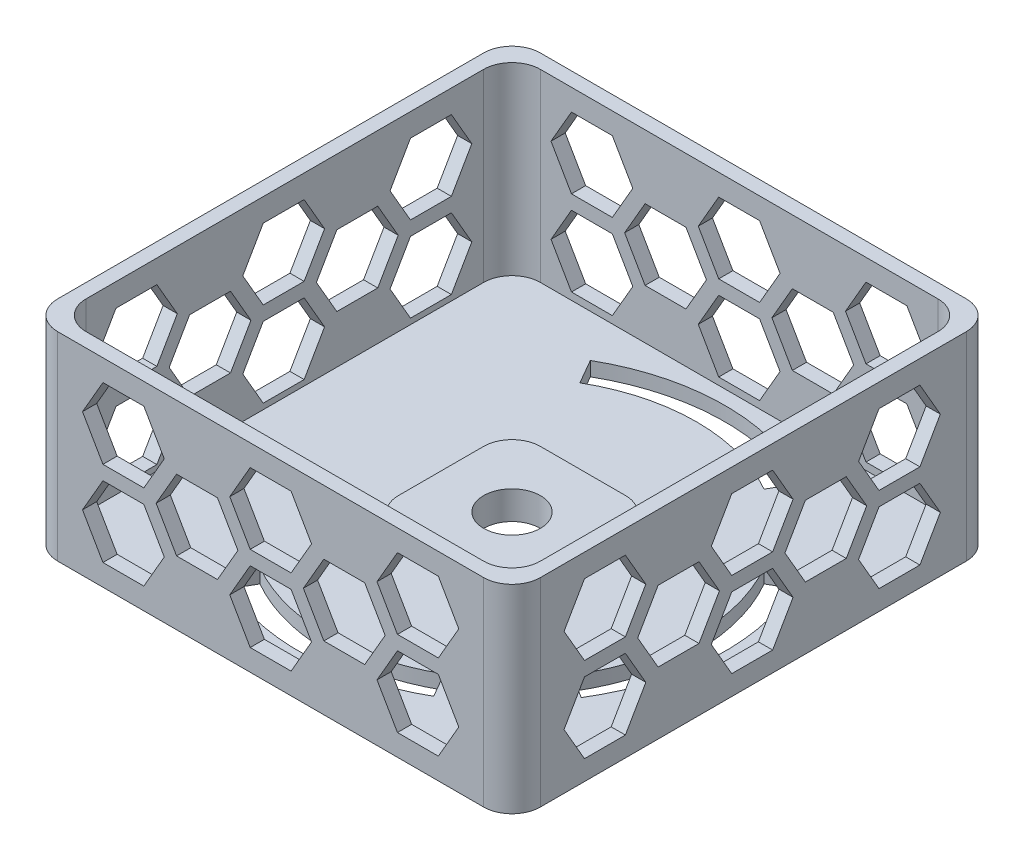
SolidWorks part; units mm, degrees
ref_plane "Front Plane" through (0, 0, 0) normal (0, 0, 1) x (1, 0, 0)
ref_plane "Top Plane" through (0, 0, 0) normal (0, 1, 0) x (1, 0, 0)
ref_plane "Right Plane" through (0, 0, 0) normal (1, 0, 0) x (0, 0, -1)
sketch "Sketch1" plane through (0, 0, 0) normal (0, 1, 0) x (1, 0, 0)
  line L0 (10, 0) -> (160, 0)
  line L1 (170, 10) -> (170, 160)
  line L2 (160, 170) -> (10, 170)
  line L3 (0, 160) -> (0, 10)
  arc A0 (10, 170) -> (0, 160) centre (10, 160) ccw
  arc A1 (170, 160) -> (160, 170) centre (160, 160) ccw
  arc A2 (160, 0) -> (170, 10) centre (160, 10) ccw
  arc A3 (10, 0) -> (0, 10) centre (10, 10) cw
  point P9 (170, 170)
  point P12 (170, 0)
  point P15 (0, 0)
  dimension "D3" = 10
  dimension "D4" = 10
  dimension "D5" = 10
  dimension "D6" = 10
  dimension "D1" = 170
  dimension "D2" = 170
extrude "Boss-Extrude1" add sketch "Sketch1" along normal blind 70
sketch "Sketch2" plane through (0, 70, 0) normal (0, 1, 0) x (1, 0, 0)
  line L0 (0, 85) -> (170, 85) construction
  line L1 (0, 160) -> (0, 10) construction
  line L2 (170, 10) -> (170, 160) construction
  line L3 (15, 5) -> (155, 5)
  line L4 (5, 15) -> (5, 155)
  line L5 (165, 15) -> (165, 155)
  line L6 (15, 165) -> (155, 165)
  line L7 (5, 5) -> (165, 165) construction
  line L8 (165, 5) -> (5, 165) construction
  line L9 (160, 170) -> (10, 170) construction
  line L10 (10, 0) -> (160, 0) construction
  arc A0 (5, 155) -> (15, 165) centre (15, 155) cw
  arc A1 (165, 155) -> (155, 165) centre (155, 155) ccw
  arc A2 (5, 15) -> (15, 5) centre (15, 15) ccw
  arc A3 (155, 5) -> (165, 15) centre (155, 15) ccw
  point P7 (85, 85)
  dimension "D5" = 10
  dimension "D6" = 10
  dimension "D7" = 10
  dimension "D8" = 10
  dimension "D1" = 5
  dimension "D2" = 5
  dimension "D3" = 5
  dimension "D4" = 5
extrude "Cut-Extrude1" cut sketch "Sketch2" against normal blind 65
sketch "Sketch5" plane through (0, 0, 0) normal (0, 0, 1) x (1, 0, 0)
  line L0 (85, 0) -> (85, 70) construction
  line L1 (10, 0) -> (160, 0) construction
  line L2 (10, 70) -> (160, 70) construction
  line L3 (10, 35) -> (160, 35) construction
  line L4 (10, 70) -> (10, 0) construction
  line L5 (160, 70) -> (160, 0) construction
  line L59 (47.5397, 49.9707) -> (40.3397, 62.4415)
  line L60 (40.3397, 62.4415) -> (25.9397, 62.4415)
  line L61 (25.9397, 62.4415) -> (18.7397, 49.9707)
  line L62 (18.7397, 49.9707) -> (25.9397, 37.5)
  line L63 (25.9397, 37.5) -> (40.3397, 37.5)
  line L64 (40.3397, 37.5) -> (47.5397, 49.9707)
  line L65 (99.4, 49.9707) -> (92.2, 62.4415)
  line L66 (92.2, 62.4415) -> (77.8, 62.4415)
  line L67 (77.8, 62.4415) -> (70.6, 49.9707)
  line L68 (70.6, 49.9707) -> (77.8, 37.5)
  line L69 (77.8, 37.5) -> (92.2, 37.5)
  line L70 (92.2, 37.5) -> (99.4, 49.9707)
  line L71 (151.2603, 49.9707) -> (144.0603, 62.4415)
  line L72 (144.0603, 62.4415) -> (129.6603, 62.4415)
  line L73 (129.6603, 62.4415) -> (122.4603, 49.9708)
  line L74 (122.4603, 49.9708) -> (129.6603, 37.5)
  line L75 (129.6603, 37.5) -> (144.0603, 37.5)
  line L76 (144.0603, 37.5) -> (151.2603, 49.9707)
  line L77 (99.4, 20.0293) -> (92.2, 32.5)
  line L78 (92.2, 32.5) -> (77.8, 32.5)
  line L79 (47.5397, 20.0293) -> (40.3397, 32.5)
  line L80 (40.3397, 32.5) -> (25.9397, 32.5)
  line L81 (25.9397, 32.5) -> (18.7397, 20.0292)
  line L82 (18.7397, 20.0292) -> (25.9397, 7.5585)
  line L83 (25.9397, 7.5585) -> (40.3397, 7.5585)
  line L84 (40.3397, 7.5585) -> (47.5397, 20.0293)
  line L85 (77.8, 32.5) -> (70.6, 20.0293)
  line L86 (70.6, 20.0293) -> (77.8, 7.5585)
  line L87 (77.8, 7.5585) -> (92.2, 7.5585)
  line L88 (92.2, 7.5585) -> (99.4, 20.0293)
  line L89 (151.2603, 20.0293) -> (144.0603, 32.5)
  line L90 (144.0603, 32.5) -> (129.6603, 32.5)
  line L91 (129.6603, 32.5) -> (122.4603, 20.0292)
  line L92 (122.4603, 20.0292) -> (129.6603, 7.5585)
  line L93 (129.6603, 7.5585) -> (144.0603, 7.5585)
  line L94 (144.0603, 7.5585) -> (151.2603, 20.0293)
  line L95 (73.4699, 35) -> (66.2699, 47.4708)
  line L96 (66.2699, 47.4708) -> (51.8699, 47.4708)
  line L97 (51.8699, 47.4708) -> (44.6699, 35)
  line L98 (44.6699, 35) -> (51.8699, 22.5292)
  line L99 (51.8699, 22.5292) -> (66.2699, 22.5292)
  line L100 (66.2699, 22.5292) -> (73.4699, 35)
  line L101 (125.3301, 35) -> (118.1301, 47.4708)
  line L102 (118.1301, 47.4708) -> (103.7301, 47.4708)
  line L103 (103.7301, 47.4708) -> (96.5301, 35)
  line L104 (96.5301, 35) -> (103.7301, 22.5292)
  line L105 (103.7301, 22.5292) -> (118.1301, 22.5292)
  line L106 (118.1301, 22.5292) -> (125.3301, 35)
  circle A4 centre (33.1397, 49.9707) radius 12.4708 construction
  circle A12 centre (85, 49.9707) radius 12.4708 construction
  circle A13 centre (136.8603, 49.9707) radius 12.4708 construction
  circle A14 centre (33.1397, 20.0292) radius 12.4708 construction
  circle A15 centre (85, 20.0292) radius 12.4708 construction
  circle A16 centre (136.8603, 20.0292) radius 12.4708 construction
  circle A17 centre (59.0699, 35) radius 12.4708 construction
  circle A18 centre (110.9301, 35) radius 12.4708 construction
extrude "Cut-Extrude2" cut sketch "Sketch5" against normal blind 195
sketch "Sketch13" plane through (170, 0, 0) normal (1, 0, 0) x (0, 0, -1)
  line L0 (84.5881, -0.5619) -> (84.5881, 69.4381) construction
  line L1 (-0.0411, 34.9136) -> (149.9589, 34.9136) construction
  line L2 (47.1278, 49.4088) -> (39.9278, 61.8796)
  line L3 (39.9278, 61.8796) -> (25.5278, 61.8796)
  line L4 (25.5278, 61.8796) -> (18.3278, 49.4088)
  line L5 (18.3278, 49.4088) -> (25.5278, 36.9381)
  line L6 (25.5278, 36.9381) -> (39.9278, 36.9381)
  line L7 (39.9278, 36.9381) -> (47.1278, 49.4088)
  line L8 (98.9881, 49.4088) -> (91.7881, 61.8796)
  line L9 (91.7881, 61.8796) -> (77.3881, 61.8796)
  line L10 (77.3881, 61.8796) -> (70.1881, 49.4088)
  line L11 (70.1881, 49.4088) -> (77.3881, 36.9381)
  line L12 (77.3881, 36.9381) -> (91.7881, 36.9381)
  line L13 (91.7881, 36.9381) -> (98.9881, 49.4088)
  line L14 (150.8484, 49.4088) -> (143.6484, 61.8796)
  line L15 (143.6484, 61.8796) -> (129.2484, 61.8796)
  line L16 (129.2484, 61.8796) -> (122.0484, 49.4088)
  line L17 (122.0484, 49.4088) -> (129.2484, 36.9381)
  line L18 (129.2484, 36.9381) -> (143.6484, 36.9381)
  line L19 (143.6484, 36.9381) -> (150.8484, 49.4088)
  line L20 (98.9881, 19.4673) -> (91.7881, 31.9381)
  line L21 (91.7881, 31.9381) -> (77.3881, 31.9381)
  line L22 (47.1278, 19.4673) -> (39.9278, 31.9381)
  line L23 (39.9278, 31.9381) -> (25.5278, 31.9381)
  line L24 (25.5278, 31.9381) -> (18.3278, 19.4673)
  line L25 (18.3278, 19.4673) -> (25.5278, 6.9966)
  line L26 (25.5278, 6.9966) -> (39.9278, 6.9966)
  line L27 (39.9278, 6.9966) -> (47.1278, 19.4673)
  line L28 (77.3881, 31.9381) -> (70.1881, 19.4673)
  line L29 (70.1881, 19.4673) -> (77.3881, 6.9966)
  line L30 (77.3881, 6.9966) -> (91.7881, 6.9966)
  line L31 (91.7881, 6.9966) -> (98.9881, 19.4673)
  line L32 (150.8484, 19.4673) -> (143.6484, 31.9381)
  line L33 (143.6484, 31.9381) -> (129.2484, 31.9381)
  line L34 (129.2484, 31.9381) -> (122.0484, 19.4673)
  line L35 (122.0484, 19.4673) -> (129.2484, 6.9966)
  line L36 (129.2484, 6.9966) -> (143.6484, 6.9966)
  line L37 (143.6484, 6.9966) -> (150.8484, 19.4673)
  line L38 (73.058, 34.4381) -> (65.858, 46.9089)
  line L39 (65.858, 46.9089) -> (51.458, 46.9089)
  line L40 (51.458, 46.9089) -> (44.258, 34.4381)
  line L41 (44.258, 34.4381) -> (51.458, 21.9673)
  line L42 (51.458, 21.9673) -> (65.858, 21.9673)
  line L43 (65.858, 21.9673) -> (73.058, 34.4381)
  line L44 (124.9183, 34.4381) -> (117.7183, 46.9089)
  line L45 (117.7183, 46.9089) -> (103.3183, 46.9089)
  line L46 (103.3183, 46.9089) -> (96.1183, 34.4381)
  line L47 (96.1183, 34.4381) -> (103.3183, 21.9673)
  line L48 (103.3183, 21.9673) -> (117.7183, 21.9673)
  line L49 (117.7183, 21.9673) -> (124.9183, 34.4381)
  circle A0 centre (32.7278, 49.4088) radius 12.4708 construction
  circle A1 centre (84.5881, 49.4088) radius 12.4708 construction
  circle A2 centre (136.4484, 49.4088) radius 12.4708 construction
  circle A3 centre (32.7278, 19.4673) radius 12.4708 construction
  circle A4 centre (84.5881, 19.4673) radius 12.4708 construction
  circle A5 centre (136.4484, 19.4673) radius 12.4708 construction
  circle A6 centre (58.658, 34.4381) radius 12.4708 construction
  circle A7 centre (110.5183, 34.4381) radius 12.4708 construction
extrude "Cut-Extrude4" cut sketch "Sketch13" against normal up to next
pattern_linear "LPattern1" count 2 spacing 50 along (-1, 0, 0) of "Cut-Extrude4"
sketch "Sketch14" plane through (0, 5, 0) normal (0, 1, 0) x (1, 0, 0)
  line L0 (5, 85) -> (165, 85) construction
  line L1 (5, 155) -> (5, 15) construction
  line L2 (165, 15) -> (165, 155) construction
  line L3 (85, 165) -> (85, 5) construction
  line L4 (155, 165) -> (15, 165) construction
  line L5 (15, 5) -> (155, 5) construction
  line L6 (85, 60) -> (100, 60)
  line L7 (110, 70) -> (110, 100)
  line L8 (100, 110) -> (70, 110)
  line L9 (60, 100) -> (60, 70)
  line L10 (70, 60) -> (85, 60)
  arc A0 (60, 70) -> (70, 60) centre (70, 70) ccw
  arc A1 (100, 60) -> (110, 70) centre (100, 70) ccw
  arc A2 (110, 100) -> (100, 110) centre (100, 100) ccw
  arc A3 (70, 110) -> (60, 100) centre (70, 100) ccw
  dimension "D5" = 10
  dimension "D1" = 25
  dimension "D2" = 25
  dimension "D3" = 50
  dimension "D4" = 25
extrude "Boss-Extrude3" add sketch "Sketch14" along normal blind 5
sketch "Sketch15" plane through (0, 10, 0) normal (0, 1, 0) x (1, 0, 0)
  line L0 (60, 85) -> (110, 85) construction
  line L1 (60, 100) -> (60, 70) construction
  line L2 (110, 70) -> (110, 100) construction
  line L3 (85, 110) -> (85, 60) construction
  line L4 (100, 110) -> (70, 110) construction
  line L5 (70, 60) -> (100, 60) construction
  line L6 (60, 85) -> (10, 85) construction
  line L7 (85, 110) -> (85, 160) construction
  line L8 (85, 60) -> (85, 10) construction
  line L9 (110, 85) -> (160, 85) construction
  line L10 (150, 85) -> (150, 122.4166) construction
  line L11 (150, 122.4166) -> (141.3333, 117.4277) construction
  line L12 (150, 85) -> (148.8082, 45.5853) construction
  line L13 (148.8082, 45.5853) -> (140.3004, 50.8406) construction
  line L14 (85, 150) -> (122.4166, 150) construction
  line L15 (122.4166, 150) -> (117.4277, 141.3333) construction
  line L16 (85, 150) -> (47.5834, 150) construction
  line L17 (47.5834, 150) -> (52.5723, 141.3333) construction
  line L18 (85, 20) -> (122.4166, 20) construction
  line L19 (122.4166, 20) -> (117.4277, 28.6667) construction
  line L20 (85, 20) -> (47.5834, 20) construction
  line L21 (47.5834, 20) -> (52.5723, 28.6667) construction
  line L22 (52.5723, 28.6667) -> (47.5834, 20)
  line L23 (122.4166, 20) -> (117.4277, 28.6667)
  line L24 (140.3004, 50.8406) -> (148.8082, 45.5853)
  line L25 (141.3333, 117.4277) -> (150, 122.4166)
  line L26 (47.5834, 150) -> (52.5723, 141.3333)
  line L27 (117.4277, 141.3333) -> (122.4166, 150)
  circle A0 centre (85, 85) radius 10
  arc A1 (148.8082, 45.5853) -> (150, 122.4166) centre (85, 85) ccw
  arc A2 (140.3004, 50.8406) -> (141.3333, 117.4277) centre (85, 85) ccw
  arc A3 (117.4277, 141.3333) -> (52.5723, 141.3333) centre (85, 85) ccw
  arc A4 (122.4166, 150) -> (47.5834, 150) centre (85, 85) ccw
  arc A5 (52.5723, 28.6667) -> (117.4277, 28.6667) centre (85, 85) ccw
  arc A6 (47.5834, 20) -> (122.4166, 20) centre (85, 85) ccw
  dimension "D1" = 20
  dimension "D2" = 150
  dimension "D3" = 10
extrude "Cut-Extrude5" cut sketch "Sketch15" against normal up to next
